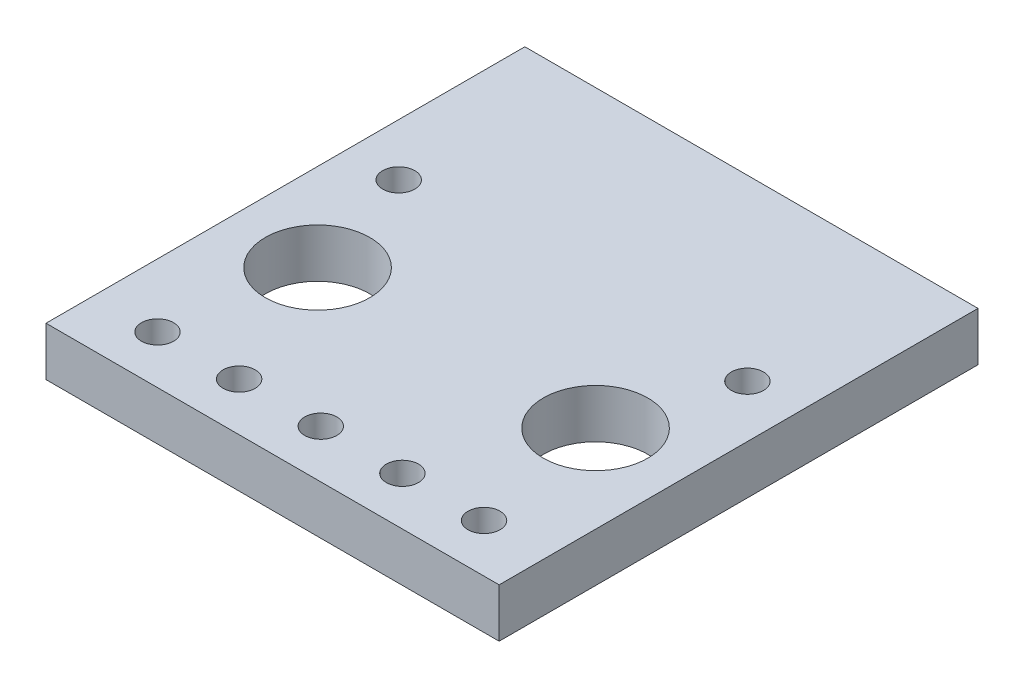
SolidWorks part; units mm, degrees
ref_plane "Front Plane" through (0, 0, 0) normal (0, 0, 1) x (1, 0, 0)
ref_plane "Top Plane" through (0, 0, 0) normal (0, 1, 0) x (1, 0, 0)
ref_plane "Right Plane" through (0, 0, 0) normal (1, 0, 0) x (0, 0, -1)
sketch "Sketch1" plane through (0, 0, 0) normal (0, 1, 0) x (1, 0, 0)
  line L1 (0, 0) -> (14.1, 0)
  line L2 (0, 0) -> (0, 14.9)
  line L3 (0, 14.9) -> (14.1, 14.9)
  line L4 (14.1, 0) -> (14.1, 14.9)
  circle A0 centre (2.725, 5.725) radius 1.625
  circle A1 centre (11.375, 5.725) radius 1.625
  circle A2 centre (1.97, 1.5) radius 0.5
  circle A3 centre (4.51, 1.5) radius 0.5
  circle A4 centre (7.05, 1.5) radius 0.5
  circle A5 centre (9.59, 1.5) radius 0.5
  circle A6 centre (12.13, 1.5) radius 0.5
  circle A7 centre (1.625, 9.35) radius 0.5
  circle A8 centre (12.475, 9.35) radius 0.5
  point P11 (7.05, 0)
  point P12 (0, 0)
  point P25 (12.6156, 11.7306)
  point P26 (0, 0)
  point P27 (0, 0)
  point P28 (0, 0)
  dimension "HoleDia" = 3.25
  dimension "D5" = 1
  dimension "D1" = 14.9
  dimension "D2" = 14.1
  dimension "HoleSpacing" = 8.65
  dimension "D3" = 5.725
  dimension "D7" = 1.5
  dimension "ShellGroundSpacing" = 10.85
  dimension "D10" = 5.55
  dimension "D4" = 4.325
  dimension "D8" = 4.325
  dimension "D9" = 4.225
  dimension "D6" = 5
extrude "Boss-Extrude1" add sketch "Sketch1" along normal blind 1.52
equation "\"HoleSpacing@Sketch1\" = 5.4 + 3.25"
equation "\"D3@Sketch1\"=4.1+\"HoleDia@Sketch1\"/2"
equation "\"D4@Sketch1\"=\"HoleSpacing@Sketch1\"/2"
